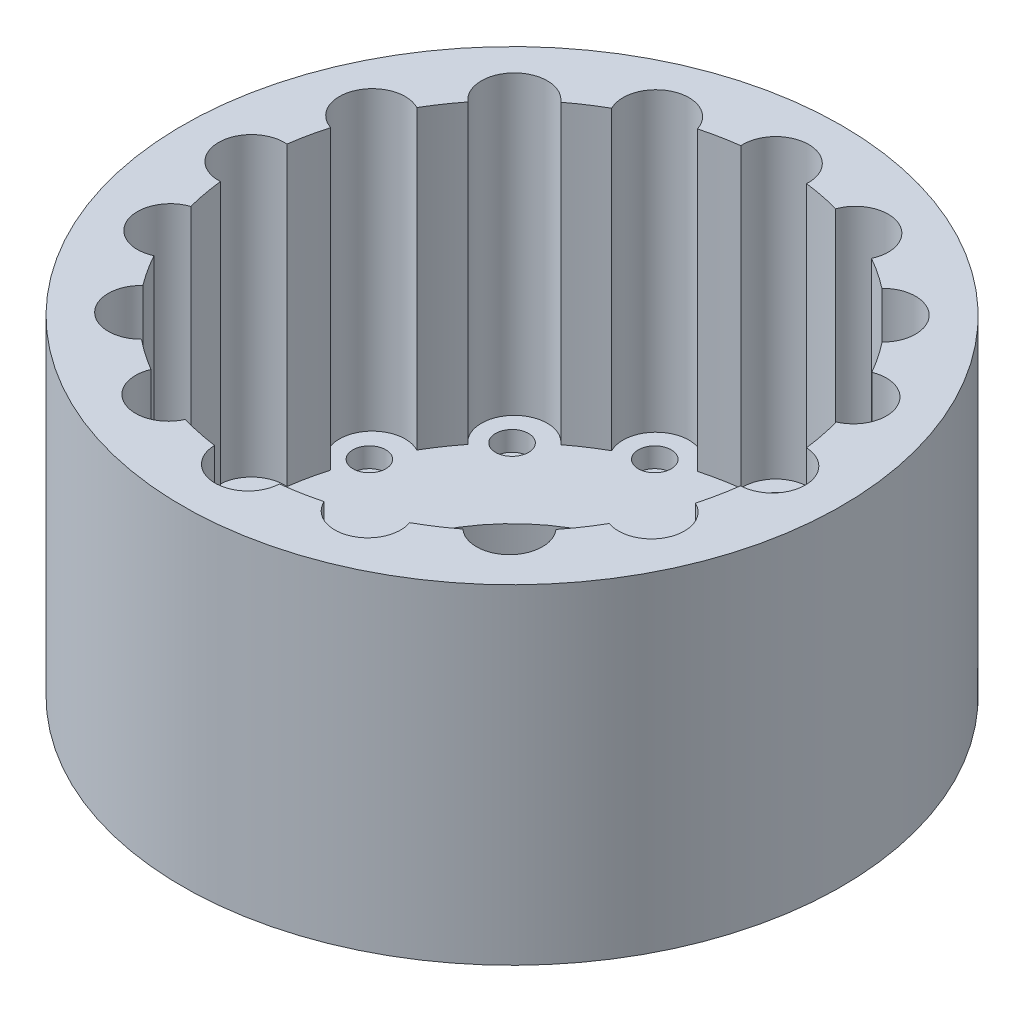
SolidWorks part; units mm, degrees
ref_plane "Front Plane" through (0, 0, 0) normal (0, 0, 1) x (1, 0, 0)
ref_plane "Top Plane" through (0, 0, 0) normal (0, 1, 0) x (1, 0, 0)
ref_plane "Right Plane" through (0, 0, 0) normal (1, 0, 0) x (0, 0, -1)
sketch "Sketch1" plane through (0, 0, 0) normal (0, 1, 0) x (1, 0, 0)
  arc A0 (-38.4721, 10.9498) -> (-39.6225, 5.4827) centre (0, 0) ccw
  arc A1 (4.9902, 39.6875) -> (-4.9902, 39.6875) centre (0, 40) ccw
  arc A2 (19.7423, 34.7885) -> (10.5038, 38.5963) centre (15.1971, 36.8722) ccw
  arc A3 (31.5425, 24.5981) -> (24.4561, 31.6528) centre (28.0405, 28.1668) ccw
  arc A4 (38.5639, 10.6218) -> (34.7247, 19.8543) centre (36.5748, 15.2091) ccw
  arc A5 (39.6831, -5.0248) -> (39.6903, 4.9683) centre (39.5008, -0.0281) ccw
  arc A6 (34.6812, -19.9303) -> (38.5373, -10.718) centre (36.373, -15.2253) ccw
  arc A7 (24.305, -31.769) -> (31.416, -24.7596) centre (27.6676, -28.0686) ccw
  arc A8 (10.1649, -38.6869) -> (19.4331, -34.9622) centre (14.7099, -36.6029) ccw
  arc A9 (-5.5266, -39.6164) -> (4.4678, -39.7497) centre (-0.5273, -39.5289) ccw
  arc A10 (-20.3279, -34.4496) -> (-11.148, -38.4151) centre (-15.7245, -36.4011) ccw
  arc A11 (-31.9737, -24.0351) -> (-25.0145, -31.2134) centre (-28.5678, -27.6957) ccw
  arc A12 (-38.7274, -10.0096) -> (-35.0397, -19.2929) centre (-37.1021, -14.7381) ccw
  arc A13 (-39.6225, 5.4827) -> (-39.7469, -4.4929) centre (-40.0281, 0.4992) ccw
  arc A14 (-34.5711, 20.1207) -> (-38.4721, 10.9498) centre (-36.9003, 15.6963) ccw
  arc A15 (-24.3492, 31.7351) -> (-31.4368, 24.7331) centre (-28.1949, 28.5397) ccw
  arc A16 (-10.477, 38.6035) -> (-19.6974, 34.814) centre (-15.2373, 37.074) ccw
  circle A17 centre (0, 0) radius 50
  arc A18 (-31.4368, 24.7331) -> (-34.5711, 20.1207) centre (0, 0) ccw
  arc A19 (-19.6974, 34.814) -> (-24.3492, 31.7351) centre (0, 0) ccw
  arc A20 (-4.9902, 39.6875) -> (-10.477, 38.6035) centre (0, 0) ccw
  arc A21 (10.5038, 38.5963) -> (4.9902, 39.6875) centre (0, 0) ccw
  arc A22 (24.4561, 31.6528) -> (19.7423, 34.7885) centre (0, 0) ccw
  arc A23 (34.7247, 19.8543) -> (31.5425, 24.5981) centre (0, 0) ccw
  arc A24 (39.6903, 4.9683) -> (38.5639, 10.6218) centre (0, 0) ccw
  arc A25 (38.5373, -10.718) -> (39.6831, -5.0248) centre (0, 0) ccw
  arc A26 (31.416, -24.7596) -> (34.6812, -19.9303) centre (0, 0) ccw
  arc A27 (19.4331, -34.9622) -> (24.305, -31.769) centre (0, 0) ccw
  arc A28 (-11.148, -38.4151) -> (-5.5266, -39.6164) centre (0, 0) ccw
  arc A29 (-25.0145, -31.2134) -> (-20.3279, -34.4496) centre (0, 0) ccw
  arc A30 (-35.0397, -19.2929) -> (-31.9737, -24.0351) centre (0, 0) ccw
  arc A31 (-39.7469, -4.4929) -> (-38.7274, -10.0096) centre (0, 0) ccw
  arc A32 (4.4678, -39.7497) -> (10.1649, -38.6869) centre (0, 0) ccw
  point P38 (-0.2637, 0.2355)
  dimension "D1" = 16
  dimension "D2" = 100
  dimension "D3" = 5
extrude "Boss-Extrude1" add sketch "Sketch1" along normal blind 45
sketch "Sketch2" plane through (0, 0, 0) normal (0, -1, 0) x (1, 0, 0)
  circle A0 centre (0, 0) radius 50
extrude "Boss-Extrude2" add sketch "Sketch2" along normal blind 5
sketch "Sketch3" plane through (0, 0, 0) normal (0, 1, 0) x (1, 0, 0)
  circle A0 centre (0, 40) radius 2.5
  circle A1 centre (15.3073, 36.9552) radius 2.5
  circle A2 centre (28.2843, 28.2843) radius 2.5
  circle A3 centre (36.9552, 15.3073) radius 2.5
  circle A4 centre (40, 0) radius 2.5
  circle A5 centre (36.9552, -15.3073) radius 2.5
  circle A6 centre (28.2843, -28.2843) radius 2.5
  circle A7 centre (15.3073, -36.9552) radius 2.5
  circle A8 centre (0, -40) radius 2.5
  circle A9 centre (-15.3073, -36.9552) radius 2.5
  circle A10 centre (-28.2843, -28.2843) radius 2.5
  circle A11 centre (-36.9552, -15.3073) radius 2.5
  circle A12 centre (-40, 0) radius 2.5
  circle A13 centre (-36.9552, 15.3073) radius 2.5
  circle A14 centre (-28.2843, 28.2843) radius 2.5
  circle A15 centre (-15.3073, 36.9552) radius 2.5
  point P35 (0, 0)
  dimension "D1" = 5
  dimension "D2" = 16
extrude "Cut-Extrude1" cut sketch "Sketch3" against normal blind 3
sketch "Sketch4" plane through (0, 0, 0) normal (0, 1, 0) x (1, 0, 0)
  circle A0 centre (0, 0) radius 25
  dimension "D1" = 50
extrude "Cut-Extrude2" cut sketch "Sketch4" against normal blind 10
